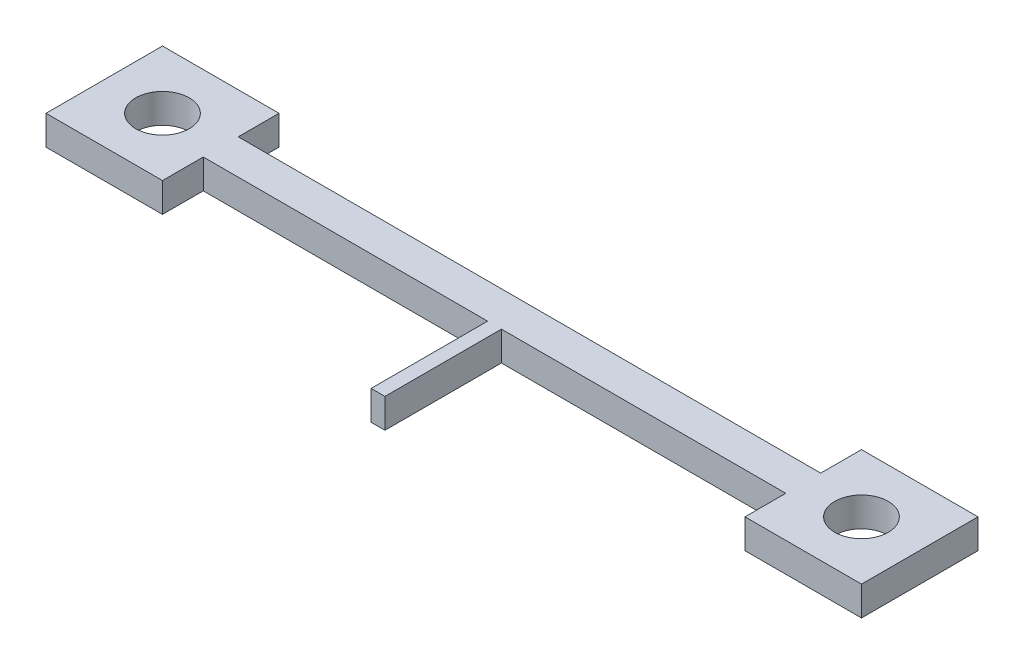
SolidWorks part; units mm, degrees
material "Commercially Pure CP-Ti UNS R50400 (SS)"
ref_plane "Front Plane" through (0, 0, 0) normal (0, 0, 1) x (1, 0, 0)
ref_plane "Top Plane" through (0, 0, 0) normal (0, 1, 0) x (1, 0, 0)
ref_plane "Right Plane" through (0, 0, 0) normal (1, 0, 0) x (0, 0, -1)
sketch "Sketch1" plane through (0, 0, 0) normal (0, 1, 0) x (1, 0, 0)
  line L0 (-41.424, -10.2833) -> (-41.424, -12.5058)
  line L1 (-47.774, -12.5058) -> (-41.424, -12.5058)
  line L2 (-47.774, -12.5058) -> (-47.774, -6.1558)
  line L3 (-47.774, -6.1558) -> (-41.424, -6.1558)
  line L4 (-3.324, -12.5058) -> (-3.324, -6.1558)
  line L7 (-41.424, -10.2833) -> (-9.674, -10.2833)
  line L9 (-41.424, -8.3783) -> (-9.674, -8.3783)
  line L13 (-41.424, -8.3783) -> (-41.424, -6.1558)
  line L14 (-9.674, -8.3783) -> (-9.674, -6.1558)
  line L15 (-9.674, -10.2833) -> (-9.674, -12.5058)
  line L16 (-9.674, -6.1558) -> (-3.324, -6.1558)
  line L17 (-9.674, -12.5058) -> (-3.324, -12.5058)
  point P0 (0, 0)
  point P6 (0, 0)
  dimension "D1" = 44.45
  dimension "D2" = 6.35
  dimension "D3" = 6.35
  dimension "D4" = 1.905
extrude "Boss-Extrude1" add sketch "Sketch1" along normal mid plane 1.6002
hole_wizard "#97 (0.0059) Diameter Hole1" positions "Sketch4" profile "Sketch3" hole size "#97" standard "Ansi Inch" end condition through all
sketch "Sketch4" plane through (0, 0.8001, 0) normal (0, 1, 0) x (-1, 0, 0)
  line L0 (47.774, 12.5058) -> (41.424, 6.1558) construction
  point P0 (44.599, 9.3308)
sketch "Sketch3" plane through (-44.599, 0.8001, 9.3308) normal (1, 0, 0) x (0, 0, 1)
  line L0 (0, 0) -> (0, 1.6002)
  line L1 (0, 1.6002) -> (1.4605, 1.6002)
  line L2 (1.4605, 1.6002) -> (1.4605, 0)
  line L5 (1.4605, 0) -> (0, 0)
  line L11 (0, -6.35) -> (0, 107.95) construction
  dimension "Thru Hole Dia." = 2.921
  dimension "Thru Hole Depth" = 1.6002
ref_plane "Plane1" through (-25.549, 0, 0) normal (1, 0, 0) x (0, 0, -1)
mirror "Mirror1" about plane through (-25.549, 0, 0) normal (1, 0, 0) of "#97 (0.0059) Diameter Hole1"
sketch "Sketch7" plane through (0, 0, 10.2833) normal (0, 0, 1) x (1, 0, 0)
  line L1 (-41.424, 0.8001) -> (-9.674, 0.8001) construction
  line L3 (-25.799, 0.8001) -> (-25.299, 0.8001)
  line L4 (-25.299, -0.8001) -> (-25.799, -0.8001)
  line L5 (-41.424, -0.8001) -> (-9.674, -0.8001) construction
  line L6 (-25.799, -0.8001) -> (-25.799, 0.8001)
  line L7 (-25.299, 0.8001) -> (-25.299, -0.8001)
extrude "Boss-Extrude2" add sketch "Sketch7" along normal blind 6.35
sketch "Sketch11" plane through (-25.799, 0, 0) normal (-1, 0, 0) x (0, 0, 1)
  line L1 (10.2833, 0.8001) -> (16.6333, 0.8001)
  line L2 (10.2833, 0.8001) -> (10.2833, -0.8001)
  line L3 (10.2833, -0.8001) -> (16.6333, -0.8001)
  line L4 (16.6333, 0.8001) -> (16.6333, -0.8001)
extrude "Boss-Extrude3" add sketch "Sketch11" along normal blind 0.127
sketch "Sketch12" plane through (-25.299, 0, 0) normal (1, 0, 0) x (0, 0, -1)
  line L1 (-10.2833, 0.8001) -> (-16.6333, 0.8001)
  line L2 (-10.2833, 0.8001) -> (-10.2833, -0.8001)
  line L3 (-10.2833, -0.8001) -> (-16.6333, -0.8001)
  line L4 (-16.6333, 0.8001) -> (-16.6333, -0.8001)
extrude "Boss-Extrude4" add sketch "Sketch12" along normal blind 0.127
